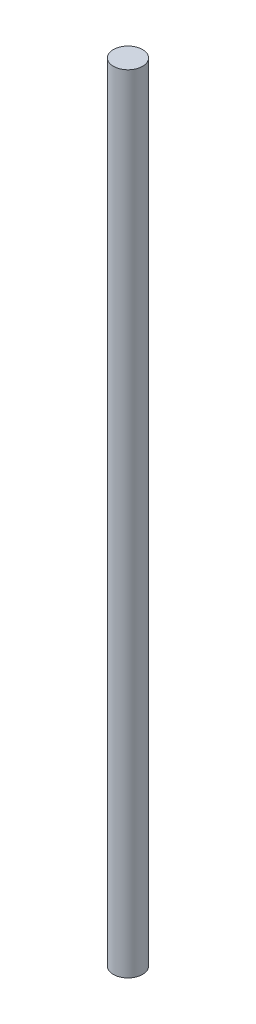
SolidWorks part; units mm, degrees
ref_plane "Front Plane" through (0, 0, 0) normal (0, 0, 1) x (1, 0, 0)
ref_plane "Top Plane" through (0, 0, 0) normal (0, 1, 0) x (1, 0, 0)
ref_plane "Right Plane" through (0, 0, 0) normal (1, 0, 0) x (0, 0, -1)
sketch "Sketch1" plane through (0, 0, 0) normal (0, 1, 0) x (1, 0, 0)
  circle A0 centre (0, 0) radius 3.175
  dimension "D1" = 6.35
extrude "Boss-Extrude1" add sketch "Sketch1" along normal blind 171.45
